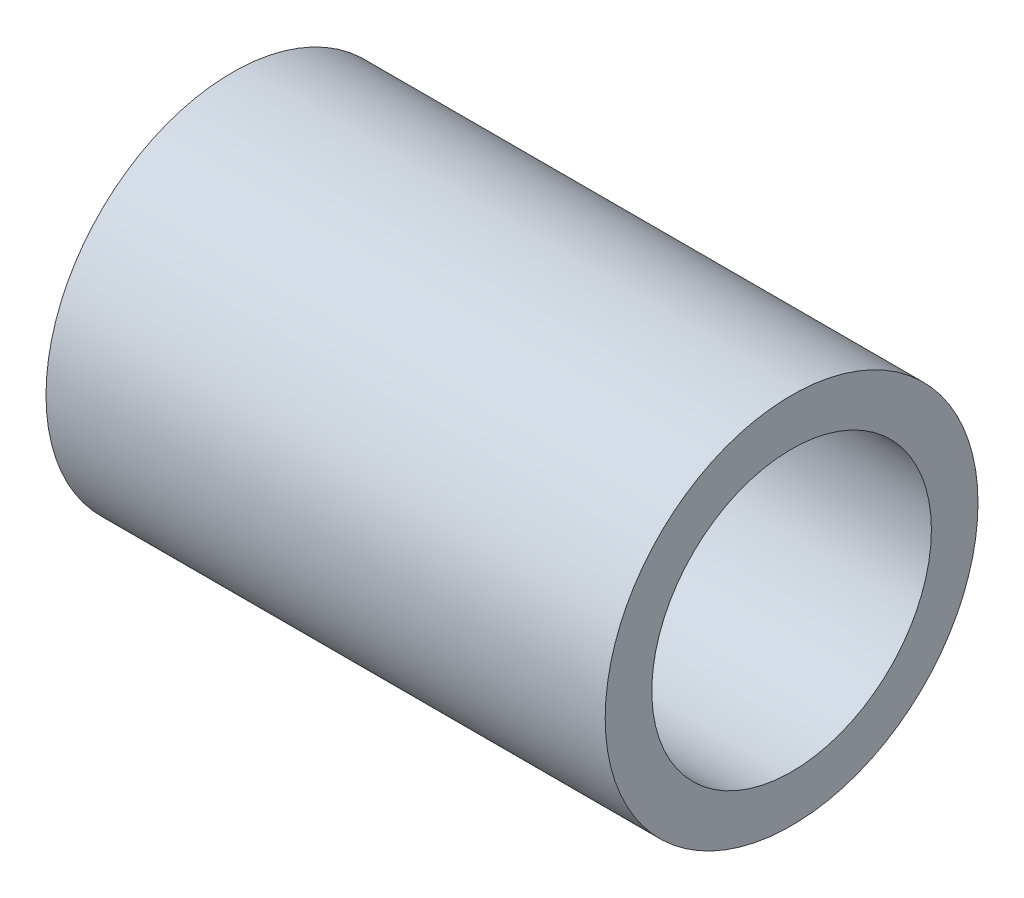
SolidWorks part; units mm, degrees
material "Brass"
ref_plane "Front Plane" through (0, 0, 0) normal (0, 0, 1) x (1, 0, 0)
ref_plane "Top Plane" through (0, 0, 0) normal (0, 1, 0) x (1, 0, 0)
ref_plane "Right Plane" through (0, 0, 0) normal (1, 0, 0) x (0, 0, -1)
sketch "Sketch1" plane through (0, 0, 0) normal (1, 0, 0) x (0, 0, -1)
  circle A0 centre (0, 0) radius 1.5
  circle A1 centre (0, 0) radius 2
  dimension "D1" = 0.5
  dimension "D2" = 3
extrude "Boss-Extrude1" add sketch "Sketch1" along normal blind 6 contours A1 | A0
